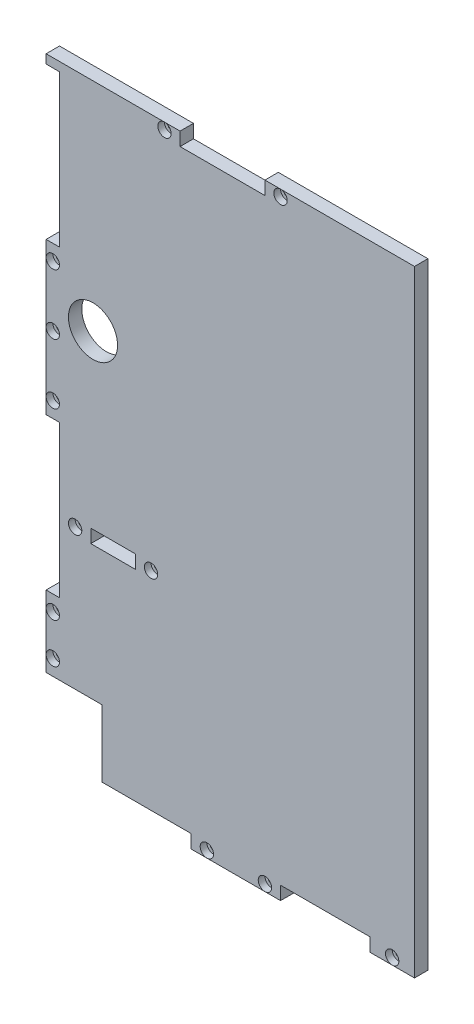
SolidWorks part; units mm, degrees
ref_plane "Plan de face" through (0, 0, 0) normal (0, 0, 1) x (1, 0, 0)
ref_plane "Plan de dessus" through (0, 0, 0) normal (0, 1, 0) x (1, 0, 0)
ref_plane "Plan de droite" through (0, 0, 0) normal (1, 0, 0) x (0, 0, -1)
sketch "Esquisse1" plane through (0, 0, 0) normal (0, 0, 1) x (1, 0, 0)
  line L1 (0, 0) -> (-165, 0)
  line L2 (0, 0) -> (0, 276)
  line L3 (0, 276) -> (-165, 276)
  line L4 (-165, 0) -> (-165, 276)
  dimension "D1" = 276
  dimension "D2" = 165
extrude "Boss.-Extru.1" add sketch "Esquisse1" along normal blind 6
sketch "Esquisse2" plane through (0, 0, 6) normal (0, 0, 1) x (1, 0, 0)
  line L8 (0, 276) -> (-165, 276) construction
  line L9 (-165, 0) -> (0, 0) construction
  line L10 (-105, 276) -> (-67, 276)
  line L11 (-105, 276) -> (-105, 270)
  line L12 (-105, 270) -> (-67, 270)
  line L13 (-165, 276) -> (-165, 0) construction
  line L14 (-165, 272) -> (-159, 272)
  line L15 (-165, 272) -> (-165, 204)
  line L16 (-165, 204) -> (-159, 204)
  line L17 (-159, 272) -> (-159, 204)
  line L19 (-165, 136) -> (-159, 136)
  line L20 (-165, 136) -> (-165, 68)
  line L21 (-165, 68) -> (-159, 68)
  line L22 (-159, 136) -> (-159, 68)
  line L23 (-140, 36) -> (-140, 6)
  line L24 (-165, 0) -> (-165, 36)
  line L25 (-165, 36) -> (-140, 36)
  line L26 (-100, 0) -> (-165, 0)
  line L27 (-20, 0) -> (-60, 0)
  line L28 (-20, 0) -> (-20, 6)
  line L29 (-20, 6) -> (-60, 6)
  line L30 (-60, 0) -> (-60, 6)
  line L31 (0, 0) -> (0, 276) construction
  line L33 (-100, 0) -> (-100, 6)
  line L34 (-100, 6) -> (-140, 6)
  line L35 (-67, 276) -> (-67, 270)
  dimension "D1" = 6
  dimension "D2" = 6
  dimension "D3" = 68
  dimension "D4" = 68
  dimension "D5" = 4
  dimension "D6" = 68
  dimension "D7" = 36
  dimension "D8" = 25
  dimension "D9" = 6
  dimension "D10" = 40
  dimension "D11" = 6
  dimension "D12" = 40
  dimension "D13" = 20
  dimension "D14" = 38
  dimension "D15" = 60
  dimension "D16" = 6
extrude "exterieur" cut sketch "Esquisse2" against normal blind 10
sketch "Esquisse3" plane through (0, 0, 6) normal (0, 0, 1) x (1, 0, 0)
  line L0 (-165, 204) -> (-159, 204) construction
  line L1 (-145, 102) -> (-125, 102)
  line L2 (-145, 102) -> (-145, 96)
  line L3 (-145, 96) -> (-125, 96)
  line L4 (-125, 102) -> (-125, 96)
  line L5 (-165, 204) -> (-165, 136) construction
  line L6 (-165, 68) -> (-165, 36) construction
  line L8 (-100, 0) -> (-60, 0) construction
  circle A0 centre (-144, 178.92) radius 11
  dimension "D1" = 22
  dimension "D2" = 20
  dimension "D4" = 21
  dimension "D3" = 6
  dimension "D5" = 25.08
  dimension "D6" = 20
  dimension "D7" = 102
extrude "Enlèv. mat.-Extru.2" cut sketch "Esquisse3" against normal through all
sketch "Esquisse4" plane through (0, 0, 6) normal (0, 0, 1) x (1, 0, 0)
  line L0 (-105, 270) -> (-67, 270) construction
  line L1 (-145, 96) -> (-125, 96) construction
  line L2 (-105, 276) -> (-105, 270) construction
  line L3 (-67, 270) -> (-67, 276) construction
  line L4 (-165, 204) -> (-159, 204) construction
  line L5 (-159, 136) -> (-165, 136) construction
  line L6 (-165, 68) -> (-159, 68) construction
  line L7 (-140, 36) -> (-165, 36) construction
  line L8 (-100, 0) -> (-100, 6) construction
  line L9 (-60, 6) -> (-60, 0) construction
  line L10 (-100, 0) -> (-60, 0) construction
  line L11 (-165, 68) -> (-165, 36) construction
  line L12 (-165, 204) -> (-165, 136) construction
  line L13 (-20, 0) -> (0, 0) construction
  line L14 (-20, 0) -> (-20, 6) construction
  line L15 (-145, 102) -> (-145, 96) construction
  line L16 (-125, 96) -> (-125, 102) construction
  circle A0 centre (-60, 273) radius 1.5
  circle A1 centre (-112, 273) radius 1.5
  circle A2 centre (-162, 197) radius 1.5
  circle A3 centre (-162, 170) radius 1.5
  circle A4 centre (-162, 143) radius 1.5
  circle A5 centre (-162, 61) radius 1.5
  circle A6 centre (-162, 43) radius 1.5
  circle A7 centre (-93, 3) radius 1.5
  circle A8 centre (-67, 3) radius 1.5
  circle A9 centre (-10, 3) radius 1.5
  circle A10 centre (-152, 99) radius 1.5
  circle A11 centre (-118, 99) radius 1.5
  point P28 (-162, 204)
  point P45 (-165, 170)
  point P46 (-10, 0)
  point P49 (-20, 3)
  dimension "D1" = 3
  dimension "D2" = 3
  dimension "D3" = 3
  dimension "D4" = 7
  dimension "D5" = 3
  dimension "D6" = 7
  dimension "D7" = 3
  dimension "D8" = 7
  dimension "D9" = 3
  dimension "D10" = 34
  dimension "D11" = 3
  dimension "D12" = 7
  dimension "D13" = 3
  dimension "D14" = 7
  dimension "D15" = 3
  dimension "D16" = 7
  dimension "D17" = 3
  dimension "D18" = 3
  dimension "D19" = 7
  dimension "D20" = 7
  dimension "D21" = 3
  dimension "D22" = 3
  dimension "D23" = 3
  dimension "D24" = 3
  dimension "D25" = 3
  dimension "D26" = 3
  dimension "D27" = 3
  dimension "D28" = 3
  dimension "D29" = 3
  dimension "D30" = 10
  dimension "D31" = 3
  dimension "D32" = 3
  dimension "D33" = 3
  dimension "D34" = 7
  dimension "D35" = 3
  dimension "D36" = 7
extrude "Enlèv. mat.-Extru.3" cut sketch "Esquisse4" against normal through all
sketch "Esquisse5" plane through (0, 0, 6) normal (0, 0, 1) x (1, 0, 0)
  circle A0 centre (-112, 273) radius 2.995
  circle A1 centre (-60, 273) radius 2.995
  circle A2 centre (-162, 197) radius 2.995
  circle A3 centre (-162, 170) radius 2.995
  circle A4 centre (-162, 143) radius 2.995
  circle A5 centre (-162, 61) radius 2.995
  circle A6 centre (-162, 43) radius 2.995
  circle A7 centre (-93, 3) radius 2.995
  circle A8 centre (-67, 3) radius 2.995
  circle A9 centre (-10, 3) radius 2.995
  circle A10 centre (-152, 99) radius 3
  circle A11 centre (-118, 99) radius 3
  dimension "D1" = 5.99
  dimension "D2" = 5.99
  dimension "D3" = 5.99
  dimension "D4" = 5.99
  dimension "D5" = 5.99
  dimension "D6" = 5.99
  dimension "D7" = 5.99
  dimension "D8" = 5.99
  dimension "D9" = 5.99
  dimension "D10" = 5.99
  dimension "D11" = 6
  dimension "D12" = 6
extrude "Enlèv. mat.-Extru.4" cut sketch "Esquisse5" against normal blind 3
